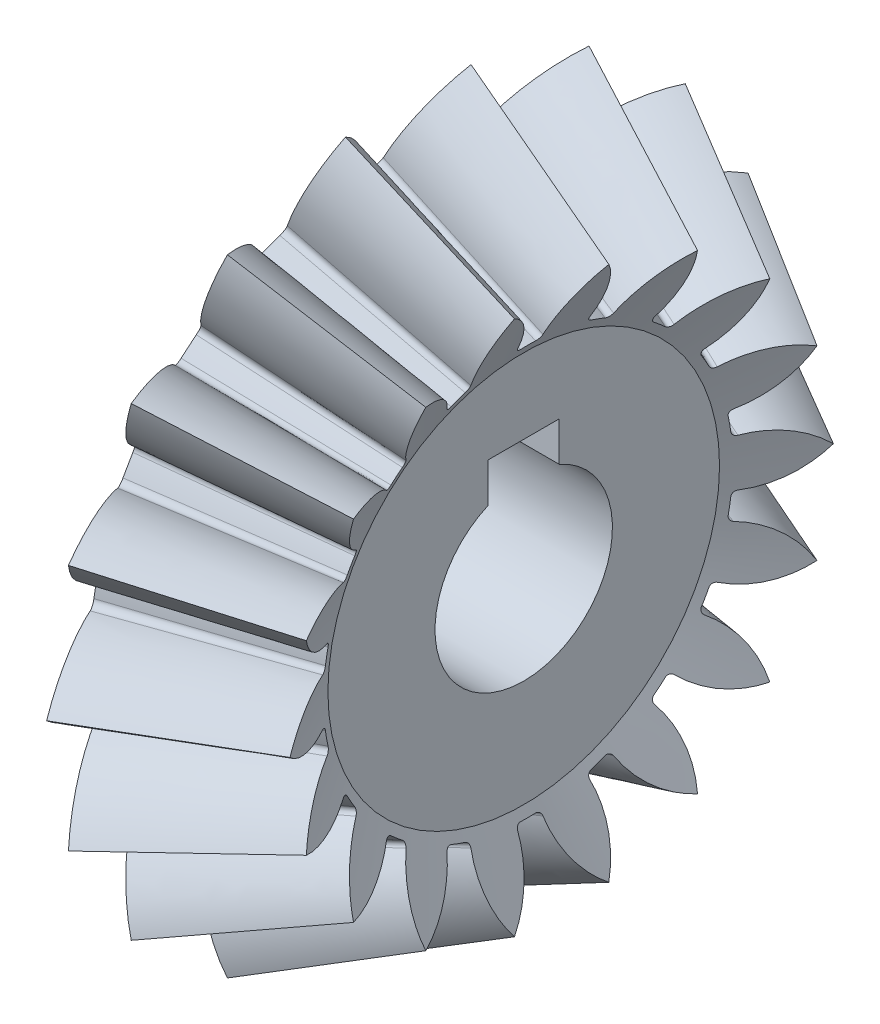
SolidWorks part; units mm, degrees
revolve "Base-Revolve" add sketch "BasProSke" angle 360 about L0
sketch "BasProSke" plane through (0, 0, 0) normal (0, 1, 0) x (1, 0, 0)
  line L0 (-10, 0) -> (60, 0) construction
  line L1 (0, 0) -> (0, 14.6841)
  line L2 (0, 0) -> (9.3562, 0)
  line L3 (9.3562, 0) -> (9.3562, 11.0358)
  line L4 (37.6579, 0) -> (-26.7039, 32.1809) construction
  line L5 (0, 14.6841) -> (3.7867, 22.2575)
  line L6 (37.6579, 0) -> (-55.7883, 61.4054) construction
  line L7 (37.6579, 0) -> (0, 14.6841) construction
  line L8 (3.7867, 22.2575) -> (12.2021, 16.7276)
  line L9 (12.2021, 16.7276) -> (9.3562, 11.0358)
  line L10 (1.6579, 18) -> (-10.3264, 18) construction
  dimension "Addendum" = 4.76
  dimension "Pitch_rad" = 18
  dimension "Dedendum_plus" = 3.7072
  dimension "Face_wid" = 10
  dimension "Pitch_ang" = 26.565
  dimension "D1" = 29.3683
  dimension "D2" = 37.6579
  dimension "D3" = 40.2492
  dimension "D4" = 6.745
ref_plane "Plane1" through (0, 0, 0) normal (0, 0, 1) x (1, 0, 0)
ref_plane "Plane2" through (0, 0, 0) normal (0, 1, 0) x (1, 0, 0)
ref_plane "Plane3" through (0, 0, 0) normal (1, 0, 0) x (0, 0, -1)
sketch "HoldingSke" plane through (0, 0, 0) normal (0, 1, 0) x (1, 0, 0)
  line L0 (0, 0) -> (0.4755, -0.1545)
  line L1 (-15, 0) -> (100, 0) construction
  line L2 (0, 0) -> (-69.8899, 60.9302)
  line L3 (0, 0) -> (-11.863, 4.5341)
  line L4 (0, 0) -> (8.2133, 2.6687)
  line L5 (0, 0) -> (-9.3695, -3.4946)
  line L6 (0, 0) -> (-10.5278, -7.1032)
  line L7 (-69.8899, 60.9302) -> (-54.3152, 95.2165)
  line L8 (-76.2, 2) -> (-74.4, 2)
  line L9 (-71.009, 38.7566) -> (-53.1078, 45.2721)
  line L10 (-76.2, 71.12) -> (104.1128, 71.12)
  line L11 (0, 0) -> (-10, 0)
  line L12 (-76.2, 101.6) -> (-76.133, 101.6)
  line L13 (24.9733, 27.94) -> (52.932, 29.102)
  line L14 (24.9733, 27.94) -> (24.9743, 27.94)
  line L15 (24.9733, 27.94) -> (100.3933, 29.8918)
  line L16 (-69.8899, 60.9302) -> (34.5601, -14.9572)
  circle A0 centre (0, 0) radius 5
  circle A1 centre (0, 0) radius 5
  circle A2 centre (0, 0) radius 5
  circle A3 centre (0, 0) radius 5
  dimension "MHD" = 10
  dimension "Hub_dia" = 10
  dimension "Bore" = 10
  dimension "MBD" = 10
  dimension "Num_teeth" = 18
  dimension "Pitch" = 0.5
  dimension "Mounting_dist" = 10
  dimension "Show_teeth" = 18
  dimension "Thickness" = 12.7
  dimension "OAL" = 37.658
  dimension "T_dim" = 1.8
  dimension "Ap" = 20
  dimension "H" = 19.05
  dimension "Pitch_radius" = 180.3128
  dimension "Width" = 10
  dimension "Backlash" = 0.067
  dimension "Addendum_fac" = 2.38
  dimension "Dedendum_fac" = 1.482
  dimension "Clearance_fac" = 0.188
  dimension "Dedendum_add" = 0.001
  dimension "Mating_teeth" = 36
  dimension "MnMD" = 37.6579
  dimension "Module" = 2
ref_plane "ToothPln" through (1.8933, 18.4708, 0) normal (-0.8944, 0.4472, 0) x (0, 0, -1)
ref_plane "ToothPln2" through (30.1263, -15.0632, 0) normal (-0.8944, 0.4472, 0) x (0, 0, 1)
sketch "TooCutSke" plane through (1.8933, 18.4708, 0) normal (-0.8944, 0.4472, 0) x (0, 0, -1)
  line L2 (0, 18.5264) -> (294.5929, -1652.193) construction
  line L3 (0, 18.5264) -> (158.8975, -1759.4202) construction
  line L4 (0, -15.621) -> (0, 105.791) construction
  line L6 (-24.765, -4.2336) -> (21.082, -4.2336) construction
  line L7 (3.1257, 0.7998) -> (1.5965, 0.6632) construction
  arc A0 (-7.4173, -3.472) -> (7.4173, -3.472) centre (0, 18.5264) ccw
  arc A1 (-0.5583, 3.5025) -> (0.5583, 3.5025) centre (0, 18.5264) ccw
  circle A2 centre (0, 18.5264) radius 18 construction
  circle A3 centre (0, 18.5264) radius 16.9145 construction
  arc A4 (0.9482, 3.154) -> (0.5583, 3.5025) centre (0.5723, 3.1258) ccw
  arc A5 (0.9482, 3.154) -> (7.4173, -3.472) centre (8.128, 3.6928) ccw
  arc A6 (-7.4173, -3.472) -> (-0.9482, 3.154) centre (-8.128, 3.6928) ccw
  arc A7 (-0.5583, 3.5025) -> (-0.9482, 3.154) centre (-0.5723, 3.1258) ccw
  ellipse E0 centre (0, 15.6741) end of major axis (22.2575, 15.6741) minor radius 19.9077 construction
sketch "TooCutSke2" plane through (30.1263, -15.0632, 0) normal (-0.8944, 0.4472, 0) x (0, 0, 1)
  line L0 (0, 0) -> (0, 68.072) construction
  line L2 (21.082, 13.1339) -> (-20.32, 13.1339) construction
  circle A0 centre (0, 16.8411) radius 0.0127
  ellipse E1 centre (0, 0) end of major axis (-14.6841, 0) minor radius 13.1339 construction
  dimension "Dedendum_plus" = 3.7072
loft "ToothCut" cut profiles "TooCutSke2", "TooCutSke"
pattern_circular "TeethCuts" count 18 every 20 about axis through (-10, 0, 0) along (1, 0, 0) of "ToothCut"
sketch "HubSke" plane through (0, 0, 0) normal (-1, 0, 0) x (0, 0, 1)
  circle A0 centre (0, 0) radius 5
  dimension "Diameter" = 10
extrude "Hub" add sketch "HubSke" along normal blind 0.0001
sketch "BorSke" plane through (0, 0, 0) normal (1, 0, 0) x (0, 0, -1)
  circle A0 centre (0, 0) radius 5
  dimension "Diameter" = 10
extrude "Bore" cut sketch "BorSke" along normal mid plane 75.316
sketch "KeySke" plane through (0, 0, 0) normal (1, 0, 0) x (0, 0, -1)
  line L0 (-2, 0) -> (-2, 6.8)
  line L1 (-2, 6.8) -> (2, 6.8)
  line L2 (2, 6.8) -> (2, 0)
  line L3 (0, 0) -> (0, 34) construction
  line L4 (-2, 0) -> (2, 0)
  dimension "Offset" = 6.8
extrude "Keyway" cut sketch "KeySke" along normal mid plane 75.316
pattern_circular "Keyway2" [suppressed] count 2 every 90 about axis through (-10, 0, 0) along (1, 0, 0)
equation "' \"Module@HoldingSke\" = 6.35"
equation "' \"Num_teeth@HoldingSke\" = 20"
equation "' \"Mating_teeth@HoldingSke\" = 12"
equation "' \"Ap@HoldingSke\" =  20"
equation "' \"Ap@HoldingSke\" = 20"
equation "' \"Width@HoldingSke\" = 0.5 * 25.4"
equation "' \"Hub_dia@HoldingSke\"= 2 * 25.4"
equation "' \"Hub_dia@HoldingSke\" = 2 * 25.4"
equation "' \"Mounting_dist@HoldingSke\" = 3 * 25.4"
equation "' \"Bore@HoldingSke\" = 19"
equation "' \"T_dim@HoldingSke\" = 0.1 * 25.4"
equation "' \"Width@KeySke\" = 0.25 * 25.4"
equation "' \"Show_teeth@HoldingSke\" = 100"
equation "' \"Backlash@HoldingSke\" = 0.009 * 25.4"
equation "' \"Addendum_fac@HoldingSke\" = 1.0"
equation "' \"Dedendum_fac@HoldingSke\" = 1.188"
equation "' \"Dedendum_add@HoldingSke\" = 0.002 * 25.4"
equation "' \"Clearance_fac@HoldingSke\" = 0.188"
equation "\"Pitch@HoldingSke\" = 1 / \"Module@HoldingSke\""
equation " \"Addendum_fac@HoldingSke\" = 0.54 + 0.46 / (\"Num_teeth@HoldingSke\" /  \"Mating_teeth@HoldingSke\" ) ^ 2"
equation "' \"Addendum_fac@HoldingSke\" = 2 - (0.54 + 0.46 / (\"Mating_teeth@HoldingSke\" /  \"Num_teeth@HoldingSke\" ) ^ 2)"
equation "\"Dedendum_fac@HoldingSke\" = 2.188 - \"Addendum_fac@HoldingSke\""
equation "\"Pitch_rad@BasProSke\" = \"Num_teeth@HoldingSke\" / \"Pitch@HoldingSke\" / 2"
equation "\"Pitch_ang@BasProSke\" = atn(\"Num_teeth@HoldingSke\" / \"Mating_teeth@HoldingSke\") * (180 / 3.14159265)"
equation "\"Addendum@BasProSke\" = \"Addendum_fac@HoldingSke\" / \"Pitch@HoldingSke\""
equation "\"Dedendum_plus@BasProSke\" = (\"Dedendum_fac@HoldingSke\" / \"Pitch@HoldingSke\" + \"Dedendum_add@HoldingSke\") * 1.25"
equation "\"Face_wid@BasProSke\" = \"Width@HoldingSke\""
equation "\"Radius@TooCutSke\" = ((\"Num_teeth@HoldingSke\" + 2 * \"Addendum_fac@HoldingSke\") / \"Pitch@HoldingSke\" ) / 2"
equation "\"Overcut_dia@TooCutSke\" =  1.02 * (\"Num_teeth@HoldingSke\" + 2 * \"Addendum_fac@HoldingSke\") / \"Pitch@HoldingSke\""
equation "\"Pitch_dia@TooCutSke\" = \"Num_teeth@HoldingSke\" / \"Pitch@HoldingSke\""
equation "\"Base_dia@TooCutSke\" = \"Num_teeth@HoldingSke\" / \"Pitch@HoldingSke\" * cos((\"Ap@HoldingSke\"  * 3.14159265 / 180))"
equation "'  \"Root_dia@TooCutSke\" =  (\"Num_teeth@HoldingSke\" + 2) / \"Pitch@HoldingSke\" - 2 * (\"Addendum_fac@HoldingSke\" + \"Dedendum_fac@HoldingSke\") / \"Pitch@HoldingSke\" - \"Dedendum_add@HoldingSke\" * 2"
equation "'  \"Root_dia@TooCutSke\" = (\"Num_teeth@HoldingSke\" + 2) / \"Pitch@HoldingSke\" - 2 * (\"Addendum_fac@HoldingSke\" + \"Dedendum_fac@HoldingSke\") / \"Pitch@HoldingSke\" - \"Dedendum_add@HoldingSke\" * 2"
equation "\"Root_dia@TooCutSke\" =  \"Num_teeth@HoldingSke\" / \"Pitch@HoldingSke\" -  2 * \"Dedendum_fac@HoldingSke\" / \"Pitch@HoldingSke\" - \"Dedendum_add@HoldingSke\" * 2"
equation "\"Half_ang@TooCutSke\" = 180 / \"Num_teeth@HoldingSke\""
equation "\"Half_CT@TooCutSke\" = \"Num_teeth@HoldingSke\" / \"Pitch@HoldingSke\" * sin((3.14159265 / 2 / \"Num_teeth@HoldingSke\")) / 2 - 2 * \"Backlash@HoldingSke\" / 4"
equation "\"Flank_rad@TooCutSke\" = \"Num_teeth@HoldingSke\" / \"Pitch@HoldingSke\" / 5"
equation "\"Root_fillet@TooCutSke\" = \"Clearance_fac@HoldingSke\" / \"Pitch@HoldingSke\" + \"Dedendum_add@HoldingSke\""
equation "\"Offset@ToothPln2\"  = \"Num_teeth@HoldingSke\" / \"Pitch@HoldingSke\" / 2 / sin(atn(\"Num_teeth@HoldingSke\" / \"Mating_teeth@HoldingSke\"))"
equation "\"Dedendum_plus@TooCutSke2\" = \"Dedendum_plus@BasProSke\""
equation "\"MHD@HoldingSke\" = \"Num_teeth@HoldingSke\" / \"Pitch@HoldingSke\" - 2 * \"Dedendum_plus@BasProSke\" * cos(atn(\"Num_teeth@HoldingSke\" / \"Mating_teeth@HoldingSke\"))"
equation "\"MBD@HoldingSke\" = \"Num_teeth@HoldingSke\" / \"Pitch@HoldingSke\" - 2 * \"Dedendum_plus@BasProSke\" * cos(atn(\"Num_teeth@HoldingSke\" / \"Mating_teeth@HoldingSke\")) - 0.002 * 25.4"
equation "\"MnMD@HoldingSke\" =  \"Num_teeth@HoldingSke\" / \"Pitch@HoldingSke\" / 2 / (\"Num_teeth@HoldingSke\" / \"Mating_teeth@HoldingSke\") + \"Dedendum_plus@BasProSke\" * sin(atn(\"Num_teeth@HoldingSke\" / \"Mating_teeth@HoldingSke\"))"
equation "\"OAL@HoldingSke\" = \"MnMD@HoldingSke\""
equation "\"MHD@HoldingSke\" = ((sgn( \"MHD@HoldingSke\" - \"Hub_dia@HoldingSke\" )-1)*( \"MHD@HoldingSke\" - \"Hub_dia@HoldingSke\" ))/-2+ \"Hub_dia@HoldingSke\""
equation "\"MBD@HoldingSke\" = ((sgn( \"MBD@HoldingSke\" - \"Bore@HoldingSke\" )-1)*( \"MBD@HoldingSke\" - \"Bore@HoldingSke\" ))/-2+ \"Bore@HoldingSke\""
equation "\"Face_wid@BasProSke\" = ((sgn( \"Face_wid@BasProSke\" - \"Offset@ToothPln2\" * 0.9)-1)*( \"Face_wid@BasProSke\" - \"Offset@ToothPln2\" * 0.9))/-2+ \"Offset@ToothPln2\" * 0.9"
equation "\"OAL@HoldingSke\" = ((sgn( \"OAL@HoldingSke\" - \"Mounting_dist@HoldingSke\" )+1)*( \"OAL@HoldingSke\" - \"Mounting_dist@HoldingSke\" ))/2 + \"Mounting_dist@HoldingSke\" + 0.000002 * 25.4"
equation "\"Num_teeth@TeethCuts\" = int( \"Show_teeth@HoldingSke\" ) + 1"
equation "\"Num_teeth@TeethCuts\" = ((sgn( \"Num_teeth@TeethCuts\" - \"Num_teeth@HoldingSke\" )-1)*( \"Num_teeth@TeethCuts\" - \"Num_teeth@HoldingSke\" ))/-2+ \"Num_teeth@HoldingSke\""
equation "\"Num_teeth@TeethCuts\" = ((sgn( \"Num_teeth@TeethCuts\" - 2.0)+1)*( \"Num_teeth@TeethCuts\" - 2.0))/2 +2.0"
equation "\"Angle@TeethCuts\" = 360.0 / \"Num_teeth@HoldingSke\""
equation "\"Diameter@HubSke\" = \"MHD@HoldingSke\""
equation "\"Length@Hub\" = \"OAL@HoldingSke\" - \"MnMD@HoldingSke\" + 0.000002 * 25.4"
equation "\"Diameter@BorSke\" = \"MBD@HoldingSke\""
equation "\"D1@Bore\" = \"OAL@HoldingSke\" * 2.0"
equation "\"D1@Keyway\" = \"OAL@HoldingSke\" * 2.0"
equation "\"Offset@KeySke\" = \"T_dim@HoldingSke\" + \"MBD@HoldingSke\" / 2.0"
